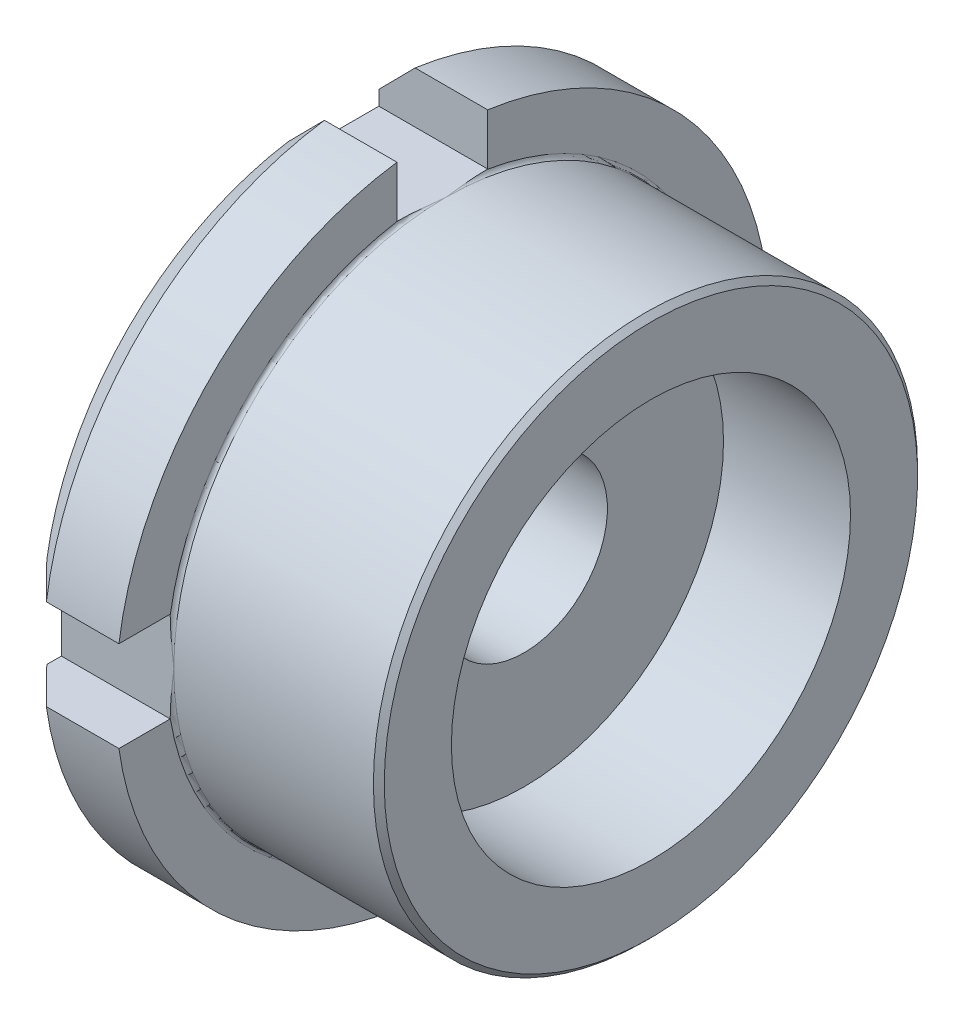
SolidWorks part; units mm, degrees
ref_plane "Front Plane" through (0, 0, 0) normal (0, 0, 1) x (1, 0, 0)
ref_plane "Top Plane" through (0, 0, 0) normal (0, 1, 0) x (1, 0, 0)
ref_plane "Right Plane" through (0, 0, 0) normal (1, 0, 0) x (0, 0, -1)
sketch "Sketch1" plane through (0, 0, 0) normal (0, 0, 1) x (1, 0, 0)
  line L0 (0, 0) -> (0, 5.5) construction
  line L11 (17.6053, 11) -> (17.6053, 15)
  line L12 (5.6053, 4.6) -> (5.6053, 9.1)
  line L14 (5.6053, 4.6) -> (10.6053, 4.6)
  line L15 (10.6053, 4.6) -> (10.6053, 11)
  line L16 (10.6053, 11) -> (17.6053, 11)
  line L17 (17.6053, 15) -> (6.3053, 15)
  line L18 (6.1053, 15.2) -> (6.1053, 18)
  line L22 (4.6053, 10.1) -> (1.1053, 10.1)
  line L28 (0.1053, 16) -> (0.1053, 11.1)
  line L29 (2.1053, 18) -> (6.1053, 18)
  line L32 (0.1053, 16) -> (2.1053, 18)
  line L33 (0, 0) -> (33.5223, 0) construction
  arc A0 (6.3053, 15) -> (6.1053, 15.2) centre (6.3053, 15.2) cw
  arc A1 (1.1053, 10.1) -> (0.1053, 11.1) centre (1.1053, 11.1) cw
  arc A2 (5.6053, 9.1) -> (4.6053, 10.1) centre (4.6053, 9.1) ccw
  point P14 (0.1053, 18)
  point P20 (0.1053, 10.1)
  point P23 (5.6053, 10.1)
  dimension "D11" = 0.2
  dimension "D12" = 1
  dimension "D13" = 1
  dimension "D1" = 5.5
  dimension "D2" = 5.5
  dimension "D3" = 2
  dimension "D4" = 11
  dimension "D5" = 15
  dimension "D6" = 6
  dimension "D7" = 7
  dimension "D8" = 17.5
  dimension "D9" = 2
  dimension "D10" = 18
  dimension "D14" = 10.5
revolve "Revolve2" add sketch "Sketch1" angle 360 about L33
sketch "Sketch5" plane through (0.1053, 0, 0) normal (-1, 0, 0) x (0, 0, 1)
  line L0 (0, 15) -> (0, 18.5083)
  line L1 (2.5, 15) -> (2.5, 18.5083)
  line L2 (-2.5, 15) -> (-2.5, 18.5083)
  line L3 (0, 18) -> (0, 15)
  line L4 (0, 15) -> (2.5, 15)
  line L5 (0, 15) -> (-2.5, 15)
  line L6 (-2.5, 15) -> (-2.5, 18.5083)
  line L7 (-2.5, 18.5083) -> (2.5, 18.5083)
  line L8 (2.5, 18.5083) -> (2.5, 15)
  line L9 (-2.5, 0) -> (-2.5, 25.8192) construction
  line L10 (0, 0) -> (0, 25.8192) construction
  line L11 (2.5, 0) -> (2.5, 25.8192) construction
  circle A0 centre (0, 0) radius 18 construction
  circle M3 centre (0, 0) radius 16
  dimension "D3" = 3
  dimension "D1" = 2.5
  dimension "D2" = 2.5
extrude "Cut-Extrude3" cut sketch "Sketch5" against normal through all contours L5 L0 L2 M3 | L0 L4 L1 M3 | L7 L0 L1 M3 | L7 L2 L0 M3
pattern_circular "CirPattern1" count 4 over 360 about axis through (0, 0, 0) along (1, 0, 0) of "Cut-Extrude3"
chamfer "Chamfer1" distance 0.3 angle 45 1 edges at (17.6053, 0, 15)
